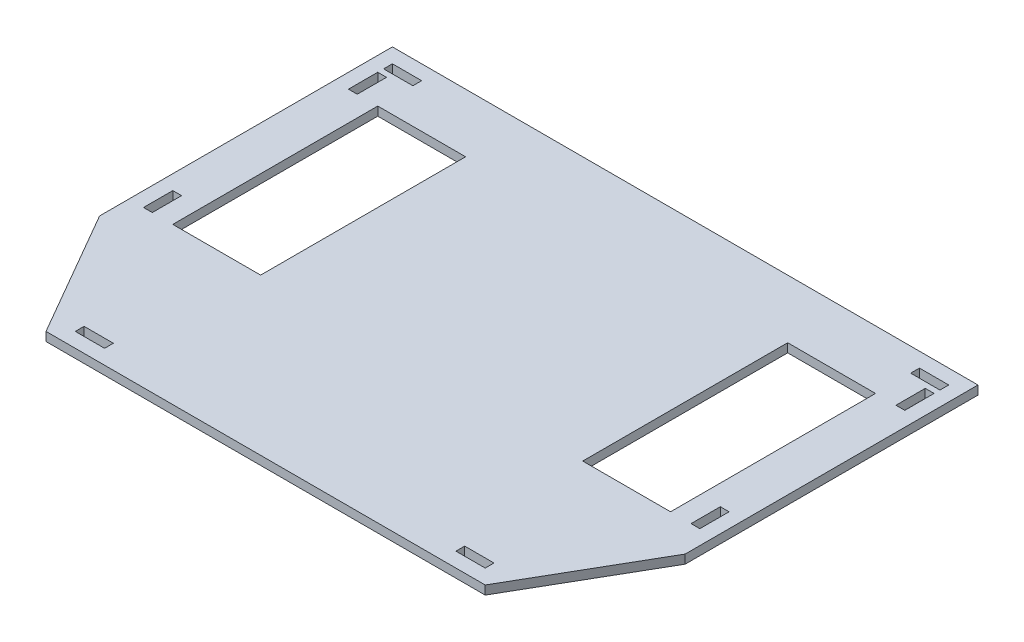
SolidWorks part; units mm, degrees
ref_plane "Plano frontal" through (0, 0, 0) normal (0, 0, 1) x (1, 0, 0)
ref_plane "Plano superior" through (0, 0, 0) normal (0, 1, 0) x (1, 0, 0)
ref_plane "Plano direito" through (0, 0, 0) normal (1, 0, 0) x (0, 0, -1)
sketch "Esboço1" plane through (0, 0, 0) normal (0, 1, 0) x (1, 0, 0)
  line L2 (0, 0) -> (0, 70)
  line L3 (0, 0) -> (0, -70)
  line L6 (-97.3576, -26.6987) -> (-97.3576, 73.3013)
  line L7 (102.6424, -26.6987) -> (102.6424, 73.3013)
  line L10 (-97.3576, 73.3013) -> (102.6424, 73.3013)
  line L11 (-97.3576, -26.6987) -> (-72.3576, -70)
  line L12 (102.6424, -26.6987) -> (77.6424, -70)
  line L13 (77.6424, -70) -> (-72.3576, -70)
  line L15 (77.6424, -26.6987) -> (102.6424, -26.6987)
  dimension "D1" = 150
  dimension "D2" = 100
  dimension "D3" = 70
  dimension "D5" = 200
  dimension "D6" = 50
  dimension "D8" = 150
extrude "Ressalto-extrusão1" add sketch "Esboço1" along normal blind 3
sketch "Esboço3" plane through (0, 3, 0) normal (0, 1, 0) x (1, 0, 0)
  line L0 (2.6424, -70) -> (2.6424, -52.3382)
  line L1 (77.6424, -70) -> (-72.3576, -70) construction
  line L2 (102.6424, -26.6987) -> (102.6424, 73.3013) construction
  line L3 (-92.3576, 68.3013) -> (-82.3576, 68.3013)
  line L4 (-92.3576, 68.3013) -> (-92.3576, 65.3013)
  line L5 (-92.3576, 65.3013) -> (-82.3576, 65.3013)
  line L6 (-82.3576, 68.3013) -> (-82.3576, 65.3013)
  line L7 (87.6424, 68.3013) -> (97.6424, 68.3013)
  line L8 (87.6424, 68.3013) -> (87.6424, 65.3013)
  line L9 (87.6424, 65.3013) -> (97.6424, 65.3013)
  line L10 (97.6424, 68.3013) -> (97.6424, 65.3013)
  line L11 (94.625, 63.3013) -> (97.6424, 63.3013)
  line L12 (94.625, 63.3013) -> (94.625, 53.3013)
  line L13 (94.625, 53.3013) -> (97.6424, 53.3013)
  line L14 (97.6424, 63.3013) -> (97.6424, 53.3013)
  line L19 (-97.3576, 73.3013) -> (102.6424, 73.3013) construction
  line L20 (-92.3576, 63.3013) -> (-89.3576, 63.3013)
  line L21 (-92.3576, 63.3013) -> (-92.3576, 53.3013)
  line L22 (-92.3576, 53.3013) -> (-89.3576, 53.3013)
  line L23 (-89.3576, 63.3013) -> (-89.3576, 53.3013)
  line L24 (-92.3576, -6.6987) -> (-89.3576, -6.6987)
  line L25 (-92.3576, -6.6987) -> (-92.3576, -16.6987)
  line L26 (-92.3576, -16.6987) -> (-89.3576, -16.6987)
  line L27 (-89.3576, -6.6987) -> (-89.3576, -16.6987)
  line L28 (-97.3576, -26.6987) -> (-97.3576, 73.3013) construction
  line L30 (94.6424, -6.6987) -> (97.6424, -6.6987)
  line L31 (94.6424, -6.6987) -> (94.6424, -16.6987)
  line L32 (94.6424, -16.6987) -> (97.6424, -16.6987)
  line L33 (97.6424, -6.6987) -> (97.6424, -16.6987)
  line L34 (-67.3576, -65) -> (-57.3576, -65)
  line L35 (-67.3576, -65) -> (-67.3576, -62)
  line L36 (-67.3576, -62) -> (-57.3576, -62)
  line L37 (-57.3576, -65) -> (-57.3576, -62)
  line L38 (72.6424, -65) -> (62.6424, -65)
  line L39 (72.6424, -65) -> (72.6424, -62)
  line L40 (72.6424, -62) -> (62.6424, -62)
  line L41 (62.6424, -65) -> (62.6424, -62)
  dimension "D1" = 5
  dimension "D2" = 5
  dimension "D3" = 3
  dimension "D4" = 3
  dimension "D5" = 5
  dimension "D6" = 10
  dimension "D7" = 5
  dimension "D8" = 10
  dimension "D9" = 10
  dimension "D10" = 10
  dimension "D11" = 5
  dimension "D12" = 10
  dimension "D13" = 10
  dimension "D14" = 3
  dimension "D15" = 5
  dimension "D16" = 5
  dimension "D17" = 3
  dimension "D18" = 10
  dimension "D19" = 10
  dimension "D20" = 5
  dimension "D21" = 3
  dimension "D22" = 10
  dimension "D23" = 10
  dimension "D24" = 5
  dimension "D25" = 5
  dimension "D26" = 3
  dimension "D27" = 10
  dimension "D28" = 3
  dimension "D29" = 10
  dimension "D30" = 5
  dimension "D31" = 5
extrude "Corte-extrusão1" cut sketch "Esboço3" against normal blind 3 contours L34 L37 L36 L35 | L41 L38 L39 L40 | L33 L30 L31 L32 | L14 L11 L12 L13 | L10 L7 L8 L9 | L27 L24 L25 L26 | L23 L20 L21 L22 | L6 L3 L4 L5
sketch "Esboço4" plane through (0, 3, 0) normal (0, 1, 0) x (1, 0, 0)
  line L0 (-97.3576, -26.6987) -> (-97.3576, 73.3013) construction
  line L1 (-82.3576, 53.3013) -> (-52.3576, 53.3013)
  line L2 (-82.3576, 53.3013) -> (-82.3576, -16.6987)
  line L3 (-82.3576, -16.6987) -> (-52.3576, -16.6987)
  line L4 (-52.3576, 53.3013) -> (-52.3576, -16.6987)
  line L5 (87.6424, 53.3013) -> (57.6424, 53.3013)
  line L6 (87.6424, 53.3013) -> (87.6424, -16.6987)
  line L7 (87.6424, -16.6987) -> (57.6424, -16.6987)
  line L8 (57.6424, 53.3013) -> (57.6424, -16.6987)
  line L9 (102.6424, -26.6987) -> (102.6424, 73.3013) construction
  dimension "D1" = 0
  dimension "D2" = 0
  dimension "D3" = 70
  dimension "D4" = 70
  dimension "D5" = 30
  dimension "D6" = 30
  dimension "D7" = 15
  dimension "D8" = 15
extrude "Corte-extrusão2" cut sketch "Esboço4" against normal blind 3 contours L2 L1 L4 L3 | L6 L5 L8 L7
sketch "Esboço7" plane through (0, 3, 0) normal (0, 1, 0) x (1, 0, 0)
  line L0 (-52.3576, 53.3013) -> (-52.3576, 18.3013)
  line L1 (-52.3576, 53.3013) -> (-52.3576, -16.6987) construction
  line L2 (57.6424, 53.3013) -> (57.6424, 18.3013)
  line L3 (57.6424, 53.3013) -> (57.6424, -16.6987) construction
